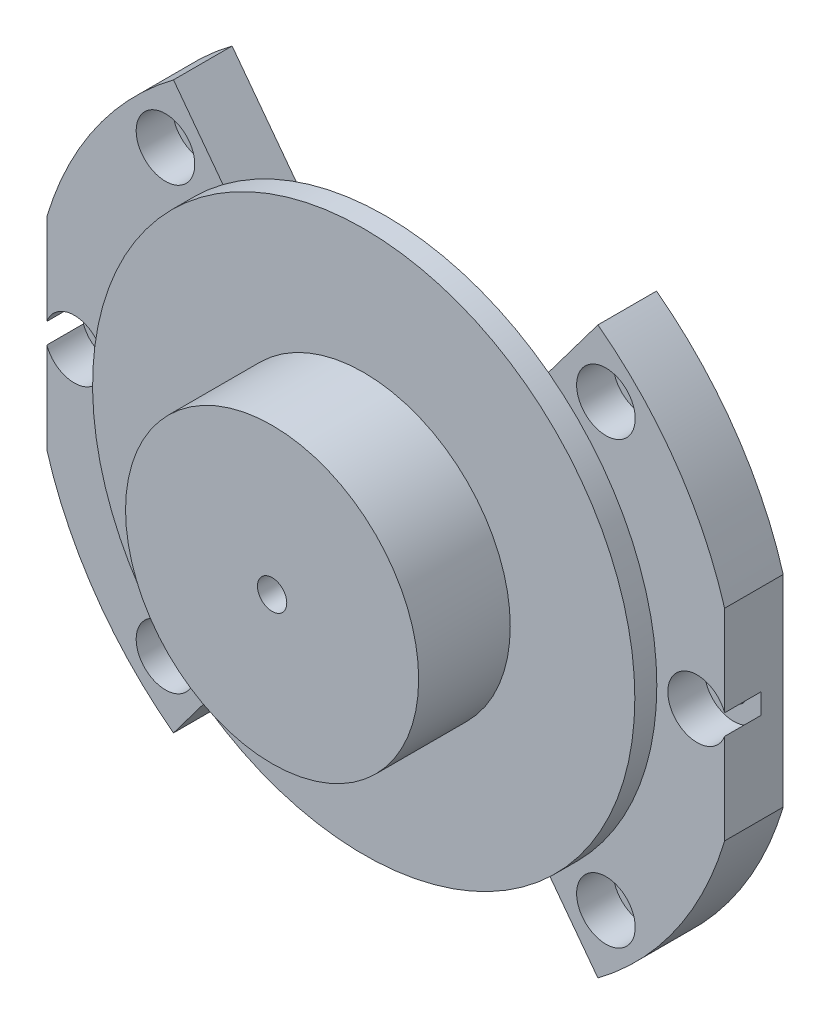
SolidWorks part; units mm, degrees
ref_plane "Front Plane" through (0, 0, 0) normal (0, 0, 1) x (1, 0, 0)
ref_plane "Top Plane" through (0, 0, 0) normal (0, 1, 0) x (1, 0, 0)
ref_plane "Right Plane" through (0, 0, 0) normal (1, 0, 0) x (0, 0, -1)
sketch "Sketch1" plane through (0, 0, 0) normal (0, 0, 1) x (1, 0, 0)
  circle A0 centre (0, 0) radius 48.25
extrude "Boss-Extrude1" add sketch "Sketch1" against normal blind 8 contours A0
sketch "Sketch2" plane through (0, 0, 0) normal (0, 0, 1) x (1, 0, 0)
  line L1 (-63.412, 28.4111) -> (-46.25, 28.4111)
  line L2 (-63.412, 28.4111) -> (-63.412, -28.4111)
  line L3 (-63.412, -28.4111) -> (-46.25, -28.4111)
  line L4 (-46.25, 28.4111) -> (-46.25, -28.4111)
  line L5 (46.25, 28.4111) -> (62.4025, 28.4111)
  line L6 (46.25, 28.4111) -> (46.25, -36.7758)
  line L7 (46.25, -36.7758) -> (62.4025, -36.7758)
  line L8 (62.4025, 28.4111) -> (62.4025, -36.7758)
  dimension "D1" = 92.5
  dimension "D2" = 46.25
extrude "Cut-Extrude1" cut sketch "Sketch2" against normal blind 8 contours L5 L8 L7 L6 | L1 L4 L3 L2
sketch "Sketch3" plane through (0, 0, 0) normal (0, 0, 1) x (1, 0, 0)
  circle A0 centre (0, 0) radius 30
extrude "Cut-Extrude2" cut sketch "Sketch3" against normal blind 8 contours A0
sketch "Sketch4" plane through (0, 0, 0) normal (0, 0, 1) x (1, 0, 0)
  circle A0 centre (-42.5, 0) radius 1.75
  dimension "D1" = 42.5
extrude "Cut-Extrude3" cut sketch "Sketch4" against normal blind 10
pattern_circular "CirPattern1" count 8 every 45 about axis through (0, 0, 0) along (0, 0, 1) of "Cut-Extrude3"
sketch "Sketch8" plane through (0, 0, 0) normal (0, 0, 1) x (1, 0, 0)
  line L0 (-28.9595, 38.5928) -> (0, 0)
  line L1 (0, 0) -> (28.9595, 38.5928)
  arc A0 (46.25, 13.7477) -> (-46.25, 13.7477) centre (0, 0) ccw construction
  arc A1 (-28.9595, 38.5928) -> (28.9595, 38.5928) centre (0, 0) cw
  circle A2 centre (-30.052, 30.052) radius 1.75 construction
  circle A3 centre (30.052, 30.052) radius 1.75 construction
  dimension "D1" = 6
  dimension "D3" = 0
  dimension "D2" = 6
extrude "Cut-Extrude4" cut sketch "Sketch8" against normal blind 10 contours L0 L1 A1
pattern_circular "CirPattern2" count 2 every 180 about axis through (0, 0, 0) along (0, 0, 1) of "Cut-Extrude4"
sketch "Sketch9" plane through (0, 0, 0) normal (0, 0, 1) x (1, 0, 0)
  circle A0 centre (-42.5, 0) radius 4
extrude "Cut-Extrude5" cut sketch "Sketch9" against normal blind 5 contours A0
pattern_circular "CirPattern3" count 8 every 45 about axis through (0, 0, 0) along (0, 0, 1) of "Cut-Extrude5"
sketch "Sketch10" plane through (0, 0, 0) normal (0, 0, 1) x (1, 0, 0)
  circle A0 centre (42.5, 0) radius 4
  circle A1 centre (30.052, 30.052) radius 4
  circle A2 centre (30.052, -30.052) radius 4
extrude "Cut-Extrude6" cut sketch "Sketch10" against normal blind 5
sketch "Sketch11" plane through (0, 0, 0) normal (0, 0, 1) x (1, 0, 0)
  circle A0 centre (0, 0) radius 37
extrude "Boss-Extrude2" add sketch "Sketch11" along normal blind 3 contours A0
sketch "Sketch12" plane through (0, 0, 3) normal (0, 0, 1) x (1, 0, 0)
  circle A0 centre (0, 0) radius 20
extrude "Boss-Extrude3" add sketch "Sketch12" along normal blind 12.5 contours A0
sketch "Sketch13" plane through (0, 0, 15.5) normal (0, 0, 1) x (1, 0, 0)
  circle A0 centre (0, 0) radius 2
extrude "Cut-Extrude8" cut sketch "Sketch13" against normal blind 38
sketch "Sketch14" plane through (0, 0, 0) normal (0, 0, -1) x (-1, 0, 0)
  line L1 (-2.0207, -3.5) -> (2.0207, -3.5)
  line L2 (2.0207, -3.5) -> (4.0415, 0)
  line L3 (4.0415, 0) -> (2.0207, 3.5)
  line L4 (2.0207, 3.5) -> (-2.0207, 3.5)
  line L5 (-2.0207, 3.5) -> (-4.0415, 0)
  line L6 (-4.0415, 0) -> (-2.0207, -3.5)
  circle A0 centre (0, 0) radius 3.5 construction
extrude "Cut-Extrude9" cut sketch "Sketch14" against normal blind 4 contours L4 L5 L6 L1 L2 L3
